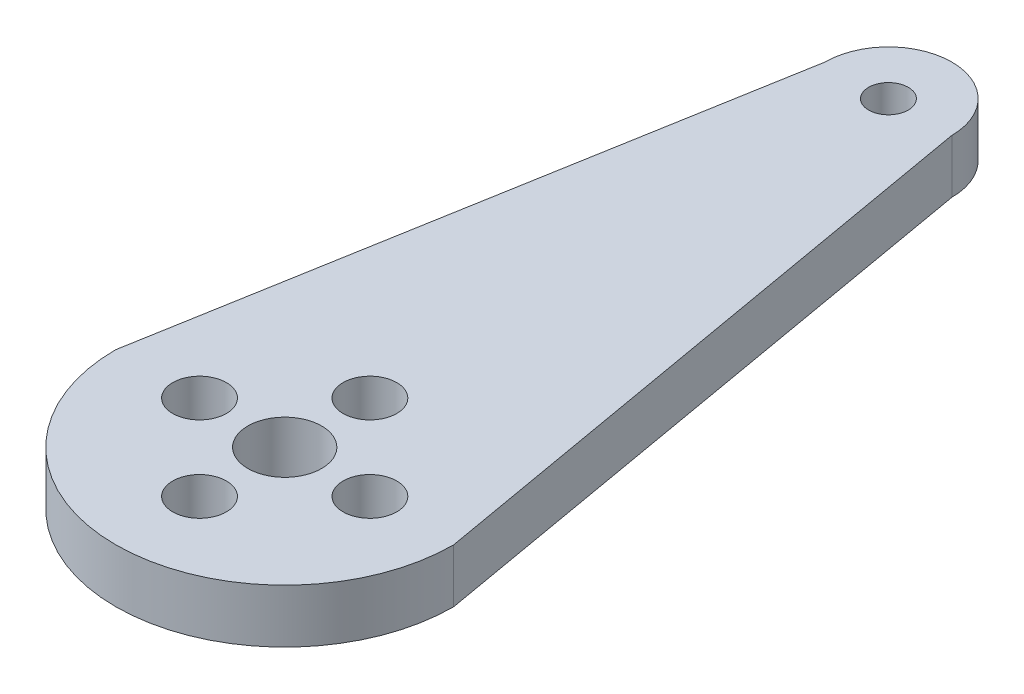
SolidWorks part; units mm, degrees
ref_plane "Front Plane" through (0, 0, 0) normal (0, 0, 1) x (1, 0, 0)
ref_plane "Top Plane" through (0, 0, 0) normal (0, 1, 0) x (1, 0, 0)
ref_plane "Right Plane" through (0, 0, 0) normal (1, 0, 0) x (0, 0, -1)
sketch "Sketch1" plane through (0, 0, 0) normal (0, 1, 0) x (1, 0, 0)
  line L0 (4.7296, 45) -> (12.5961, 0)
  circle A0 centre (0, 0) radius 2.75
  circle A1 centre (0, 6.35) radius 2
  circle A2 centre (6.35, 0) radius 2
  circle A3 centre (0, -6.35) radius 2
  circle A4 centre (-6.35, 0) radius 2
  circle A5 centre (0, 0) radius 12.5961
  circle A6 centre (0, 45) radius 1.475
  circle A7 centre (0, 45) radius 4.7296
  spline S0 degree 1 poles (-4.7296, 45) (-12.5961, 0) knots 0 0 1 1
  point P14 (0, 0)
  dimension "D1" = 5.5
  dimension "D2" = 4
  dimension "D5" = 2.95
  dimension "D3" = 6.35
  dimension "D6" = 45
  dimension "D4" = 4
extrude "Boss-Extrude1" add sketch "Sketch1" along normal blind 4 contours A7 A6 | A7 S0 A5 L0 | A5 S0 L0 A0 A1 A2 A3 A4
